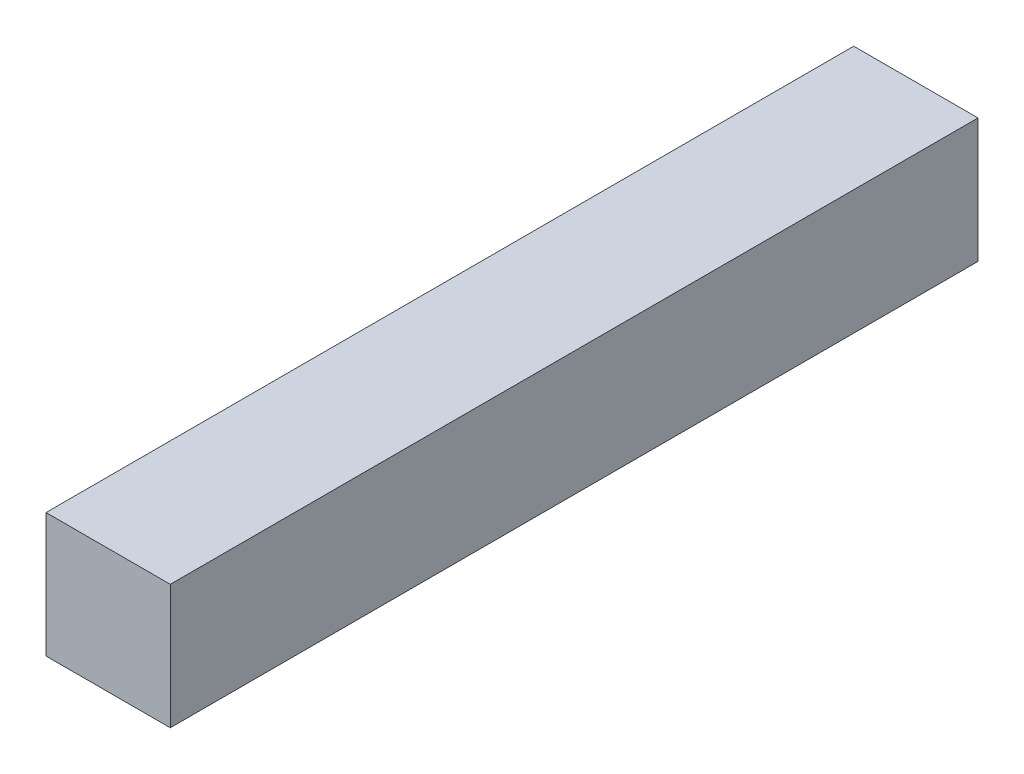
SolidWorks part; units mm, degrees
ref_plane "Спереди" through (0, 0, 0) normal (0, 0, 1) x (1, 0, 0)
ref_plane "Сверху" through (0, 0, 0) normal (0, 1, 0) x (1, 0, 0)
ref_plane "Справа" through (0, 0, 0) normal (1, 0, 0) x (0, 0, -1)
sketch "Эскиз1" plane through (0, 0, 0) normal (0, 0, 1) x (1, 0, 0)
  line L1 (-10, -10) -> (10, -10)
  line L2 (-10, -10) -> (-10, 10)
  line L3 (-10, 10) -> (10, 10)
  line L4 (10, -10) -> (10, 10)
  line L5 (-10, -10) -> (10, 10) construction
  line L6 (-10, 10) -> (10, -10) construction
  point P0 (0, 0)
  dimension "D1" = 20
extrude "Бобышка-Вытянуть1" add sketch "Эскиз1" along normal blind 130
